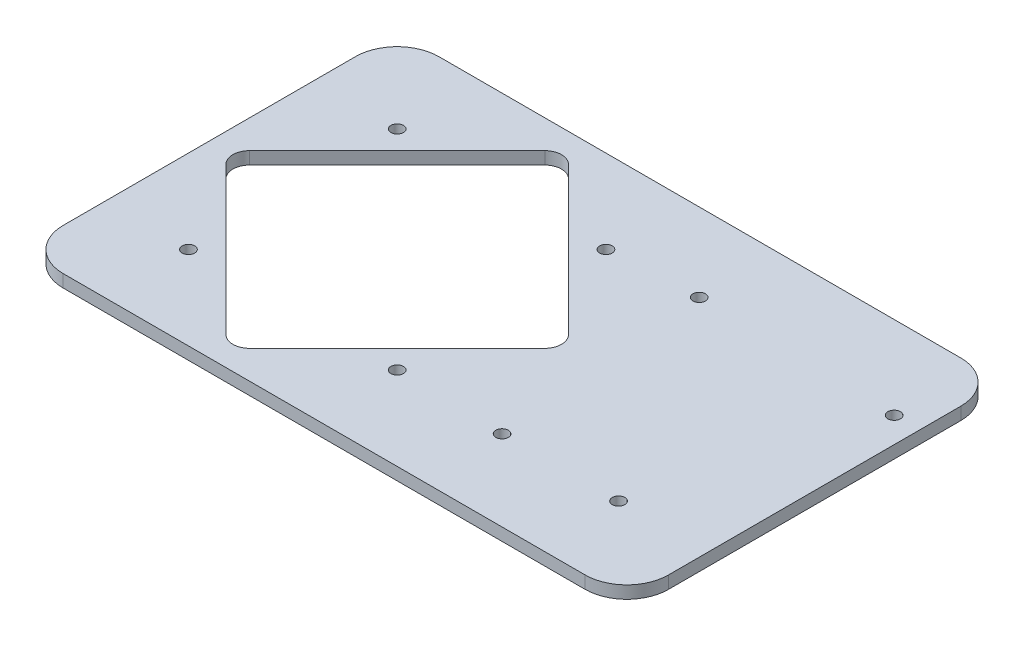
SolidWorks part; units mm, degrees
material "Acrílico (médio-alto impacto)"
ref_plane "Plano frontal" through (0, 0, 0) normal (0, 0, 1) x (1, 0, 0)
ref_plane "Plano superior" through (0, 0, 0) normal (0, 1, 0) x (1, 0, 0)
ref_plane "Plano direito" through (0, 0, 0) normal (1, 0, 0) x (0, 0, -1)
sketch "Base" plane through (0, 0, 0) normal (0, 1, 0) x (1, 0, 0)
  line L5 (-72.5, 45) -> (72.5, 45)
  line L6 (-72.5, 45) -> (-72.5, -45)
  line L7 (-72.5, -45) -> (72.5, -45)
  line L8 (72.5, 45) -> (72.5, -45)
  line L9 (0, -45) -> (0, 45) construction
  line L10 (-72.5, 0) -> (72.5, 0) construction
  line L11 (-52.5, 25) -> (-2.5, 25) construction
  line L12 (-52.5, 25) -> (-52.5, -25) construction
  line L13 (-52.5, -25) -> (-2.5, -25) construction
  line L14 (-2.5, 25) -> (-2.5, -25) construction
  line L15 (-27.5, -25) -> (-27.5, 25) construction
  line L16 (-52.5, 0) -> (-2.5, 0) construction
  point P0 (0, 0)
  point P5 (-27.5, 0)
  dimension "D1" = 90
  dimension "D2" = 145
  dimension "D3" = 50
  dimension "D4" = 45
sketch "Recorte" plane through (0, 0, 0) normal (0, 1, 0) x (1, 0, 0)
  line L0 (-68.5122, 0) -> (-27.5, 41.0122)
  line L1 (-68.5122, 0) -> (-27.5, -41.0122)
  line L2 (-27.5, 41.0122) -> (13.5122, 0)
  line L3 (-27.5, -41.0122) -> (13.5122, 0)
  line L4 (-6.9939, 20.5061) -> (-48.0061, -20.5061) construction
  line L5 (-48.0061, 20.5061) -> (-6.9939, -20.5061) construction
  line L6 (-72.5, 0) -> (72.5, 0) construction
  point P1 (-27.5, 0)
  dimension "D1" = 45
  dimension "D2" = 58
extrude "Ressalto-extrusão1" add sketch "Base" against normal blind 3
extrude "Corte-extrusão1" cut sketch "Recorte" against normal through all contours L1 L3 L2 L0
hole_wizard "Furo de diâmetro Ø3.0 (3)1" positions "Esboço3" profile "Esboço4" hole size "Ø3.0" standard "ISO" end condition through all
sketch "Esboço3" plane through (0, 0, 0) normal (0, 1, 0) x (1, 0, 0)
  point P0 (-52.5, 25)
  point P3 (-2.5, 25)
  point P6 (-2.5, -25)
  point P9 (-52.5, -25)
sketch "Esboço4" plane through (-52.5, 0, -25) normal (1, 0, 0) x (0, 0, 1)
  line L0 (0, 0) -> (0, 3)
  line L1 (0, 3) -> (1.5, 3)
  line L2 (1.5, 3) -> (1.5, 0)
  line L5 (1.5, 0) -> (0, 0)
  line L11 (0, -6.35) -> (0, 107.95) construction
  dimension "Thru Hole Dia." = 3
  dimension "Thru Hole Depth" = 3
sketch "Posição Furos Arduino Uno" plane through (0, 0, 0) normal (0, 1, 0) x (1, 0, 0)
  line L0 (72.5, -45) -> (72.5, 45) construction
  point P0 (72.5, 0)
  line B0 (66.4, 25.125) -> (18.6, 26.225)
  line B1 (23.3, -25.675) -> (51.2, -25.675)
  line B2 (51.2, -25.675) -> (66.4, 25.125)
  line B3 (42.5, 0) -> (42.5, 25.675)
  line B4 (72.5, 0) -> (42.5, 0)
  line B5 (42.5, 0) -> (42.5, -25.675)
  line B6 (72.5, -40) -> (72.5, 40)
  dimension "D1" = 30
sketch_block_instance "Posição furos-1"
sketch_block "Posição furos" parameters "D1"=47.8, "D2"=51.9, "D3"=4.7, "D4"=27.9, "D5"=1.318, "D6"=30
hole_wizard "Furo de diâmetro Ø3.0 (3)7" positions "Esboço47" profile "Esboço48" hole size "Ø3.0" standard "ISO" end condition through all
sketch "Esboço47" plane through (0, 0, 0) normal (0, 1, 0) x (1, 0, 0)
  point P0 (18.6, 26.225)
  point P3 (23.3, -25.675)
  point P6 (51.2, -25.675)
  point P9 (66.4, 25.125)
sketch "Esboço48" plane through (18.6, 0, -26.225) normal (1, 0, 0) x (0, 0, 1)
  line L0 (0, 0) -> (0, 3)
  line L1 (0, 3) -> (1.5, 3)
  line L2 (1.5, 3) -> (1.5, 0)
  line L5 (1.5, 0) -> (0, 0)
  line L11 (0, -6.35) -> (0, 107.95) construction
  dimension "Thru Hole Dia." = 3
  dimension "Thru Hole Depth" = 3
fillet "Filete1" radius 10 4 edges at (72.5, -1.5, -45) (-72.5, -1.5, -45) (-72.5, -1.5, 45) (72.5, -1.5, 45)
fillet "Filete2" radius 4 4 edges at (-27.5, -1.5, -41.0122) (13.5122, -1.5, 0) (-27.5, -1.5, 41.0122) (-68.5122, -1.5, 0)
